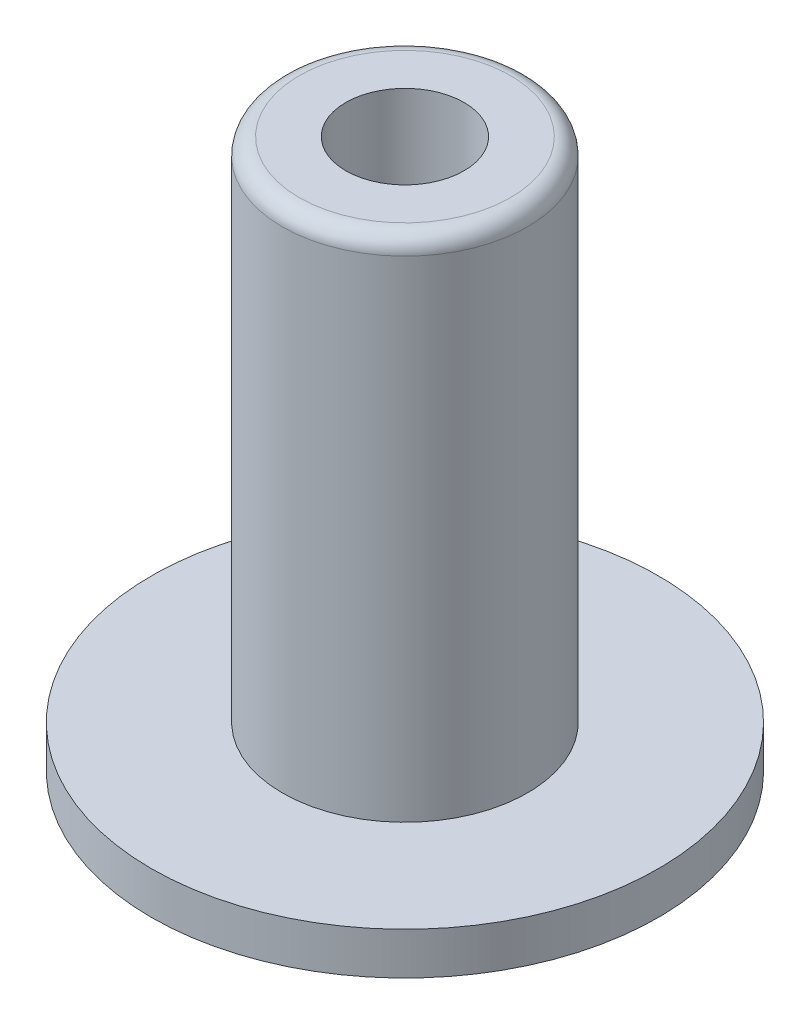
SolidWorks part; units mm, degrees
material "PET"
ref_plane "Front Plane" through (0, 0, 0) normal (0, 0, 1) x (1, 0, 0)
ref_plane "Top Plane" through (0, 0, 0) normal (0, 1, 0) x (1, 0, 0)
ref_plane "Right Plane" through (0, 0, 0) normal (1, 0, 0) x (0, 0, -1)
sketch "Sketch1" plane through (0, 0, 0) normal (0, 1, 0) x (1, 0, 0)
  circle A0 centre (0, 0) radius 3.5
  circle A1 centre (0, 0) radius 7.25
  dimension "D1" = 7
  dimension "D2" = 14.5
extrude "Boss-Extrude1" add sketch "Sketch1" along normal blind 30
sketch "Sketch2" plane through (0, 0, 0) normal (0, -1, 0) x (1, 0, 0)
  circle A0 centre (0, 0) radius 3.5
  circle A1 centre (0, 0) radius 10
  dimension "D1" = 20
extrude "Boss-Extrude2" add sketch "Sketch2" along normal blind 5
sketch "Sketch3" plane through (0, 0, 0) normal (0, 1, 0) x (1, 0, 0)
  circle A0 centre (0, 0) radius 3.5
  circle A1 centre (0, 0) radius 15
  dimension "D1" = 30
extrude "Boss-Extrude3" add sketch "Sketch3" against normal blind 2.5
fillet "Fillet1" radius 1 4 edges at (0, -5, -10) (0, 30, 7.25) (0, -5, -3.5) (0, -2.5, 10)
